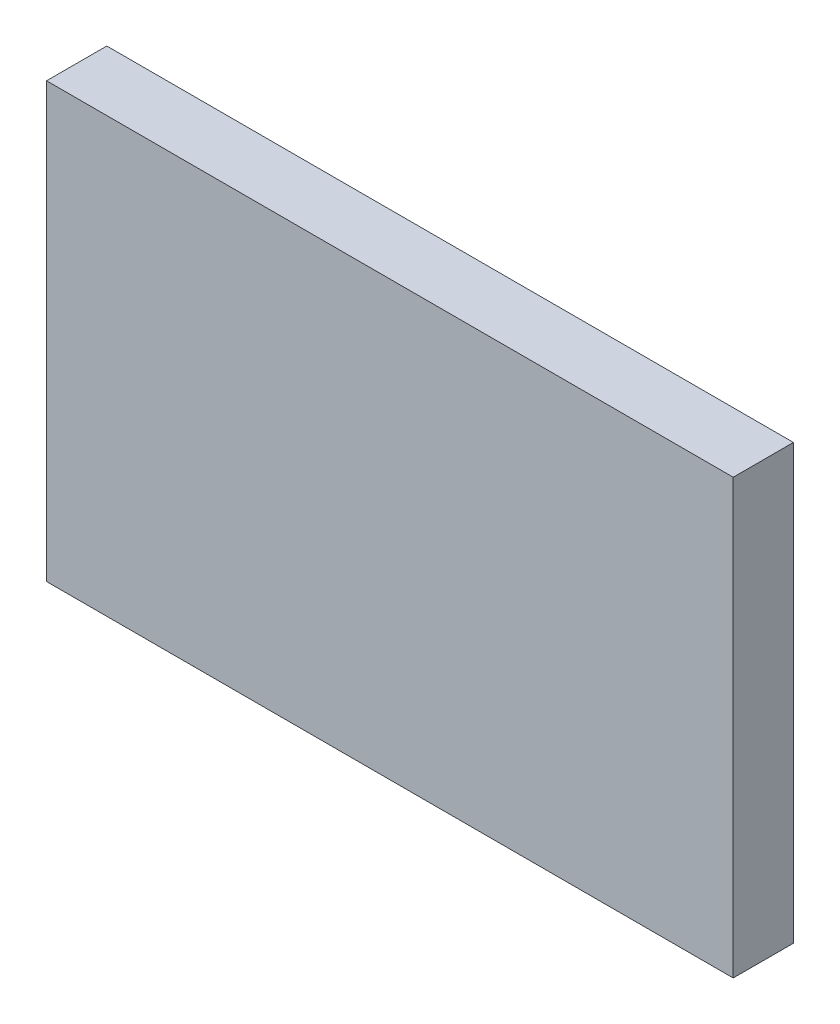
SolidWorks part; units mm, degrees
ref_plane "Front Plane" through (0, 0, 0) normal (0, 0, 1) x (1, 0, 0)
ref_plane "Top Plane" through (0, 0, 0) normal (0, 1, 0) x (1, 0, 0)
ref_plane "Right Plane" through (0, 0, 0) normal (1, 0, 0) x (0, 0, -1)
sketch "Sketch1" plane through (0, 0, 0) normal (0, 0, 1) x (1, 0, 0)
  line L1 (0, 0) -> (57, 0)
  line L2 (0, 0) -> (0, 36)
  line L3 (0, 36) -> (57, 36)
  line L4 (57, 0) -> (57, 36)
  dimension "D1" = 36
  dimension "D2" = 57
extrude "Boss-Extrude1" add sketch "Sketch1" along normal blind 5
